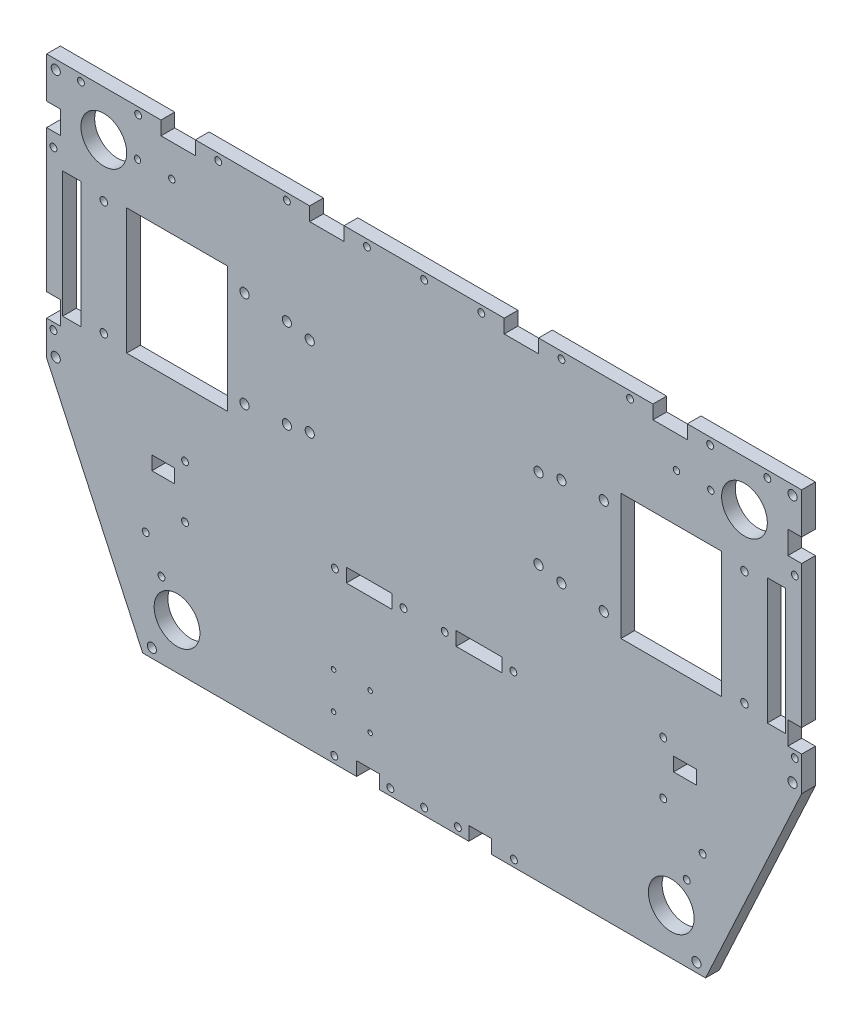
SolidWorks part; units mm, degrees
ref_plane "Plan de face" through (0, 0, 0) normal (0, 0, 1) x (1, 0, 0)
ref_plane "Plan de dessus" through (0, 0, 0) normal (0, 1, 0) x (1, 0, 0)
ref_plane "Plan de droite" through (0, 0, 0) normal (1, 0, 0) x (0, 0, -1)
sketch "Esquisse1" plane through (0, 0, 0) normal (0, 0, 1) x (1, 0, 0)
  line L0 (0, 124.9429) -> (0, -204.46) construction
  line L1 (-165, 96.73) -> (165, 96.73)
  line L2 (165, 96.73) -> (165, -18.27)
  line L3 (165, -18.27) -> (123, -109.0224)
  line L4 (123, -109.0224) -> (-123, -109.0224)
  line L5 (-211.9802, 0) -> (248.5953, 0) construction
  line L6 (-123, -109.0224) -> (-165, -18.27)
  line L7 (-165, -18.27) -> (-165, 96.73)
  line L8 (32.2623, 96.73) -> (32.2623, -70.27) construction
  circle A0 centre (-23.6, -89.5224) radius 1
  circle A1 centre (-23.6, -73.5224) radius 1
  circle A2 centre (-39.6, -89.5224) radius 1
  circle A3 centre (-39.6, -73.5224) radius 1
  dimension "D15" = 2
  dimension "D16" = 2
  dimension "D17" = 2
  dimension "D18" = 2
  dimension "D24" = 83.4
  dimension "D2" = 165
  dimension "D3" = 330
  dimension "D4" = 100
  dimension "D5" = 115
  dimension "D6" = 100
  dimension "D7" = 246
  dimension "D8" = 205.7524
  dimension "D9" = 96.73
  dimension "D10" = 115
  dimension "D11" = 167
  dimension "D19" = 19.5
  dimension "D20" = 16
  dimension "D21" = 16
  dimension "D22" = 16
  dimension "D23" = 16
extrude "Boss.-Extru.1" add sketch "Esquisse1" along normal blind 6
sketch "Esquisse2" plane through (0, 0, 6) normal (0, 0, 1) x (1, 0, 0)
  line L0 (-123, -109.0224) -> (123, -109.0224) construction
  line L1 (-158, 55.9776) -> (-150, 55.9776)
  line L2 (-158, 55.9776) -> (-158, 0.9776)
  line L3 (-158, 0.9776) -> (-150, 0.9776)
  line L4 (-150, 55.9776) -> (-150, 0.9776)
  line L5 (-130, 55.9776) -> (-86, 55.9776)
  line L6 (-130, 55.9776) -> (-130, 0.9776)
  line L7 (-130, 0.9776) -> (-86, 0.9776)
  line L8 (-86, 55.9776) -> (-86, 0.9776)
  line L9 (0, 145.0258) -> (0, -189.2208) construction
  line L10 (86, 55.9776) -> (86, 0.9776)
  line L11 (130, 0.9776) -> (86, 0.9776)
  line L12 (130, 55.9776) -> (130, 0.9776)
  line L13 (130, 55.9776) -> (86, 55.9776)
  line L14 (150, 55.9776) -> (150, 0.9776)
  line L15 (158, 0.9776) -> (150, 0.9776)
  line L16 (158, 55.9776) -> (158, 0.9776)
  line L17 (158, 55.9776) -> (150, 55.9776)
  line L18 (108, -89.0224) -> (127.6841, -51.1231) construction
  line L27 (-165, 96.73) -> (-165, -18.27) construction
  line L28 (-123, -109.0224) -> (123, -109.0224) construction
  line L29 (165, -18.27) -> (165, 96.73) construction
  line L30 (165, 96.73) -> (-165, 96.73) construction
  circle A0 centre (140, 76.73) radius 10
  circle A1 centre (108, -89.0224) radius 10
  circle A2 centre (-140, 76.73) radius 10
  circle A3 centre (-108, -89.0224) radius 10
  circle A4 centre (161, -16.0224) radius 2
  circle A5 centre (119, -105.0224) radius 2
  circle A6 centre (161, 92.73) radius 2
  circle A7 centre (-161, 92.73) radius 2
  circle A8 centre (-161, -16.0224) radius 2
  circle A9 centre (-119, -105.0224) radius 2
  circle A10 centre (125.27, 76.73) radius 1.4
  circle A11 centre (110.27, 76.73) radius 1.4
  circle A12 centre (114.7893, -75.9504) radius 1.5
  circle A13 centre (121.7031, -62.6388) radius 1.5
  circle A14 centre (-110.27, 76.73) radius 1.4
  circle A15 centre (-125.27, 76.73) radius 1.4
  circle A16 centre (-121.7031, -62.6388) radius 1.5
  circle A17 centre (-114.7893, -75.9504) radius 1.5
  dimension "D16" = 20
  dimension "D17" = 20
  dimension "D18" = 15
  dimension "D19" = 20
  dimension "D20" = 25
  dimension "D21" = 20
  dimension "D24" = 4
  dimension "D15" = 4
  dimension "D25" = 4
  dimension "D28" = 4
  dimension "D29" = 4
  dimension "D30" = 2.8
  dimension "D31" = 2.8
  dimension "D34" = 3
  dimension "D35" = 3
  dimension "D2" = 8
  dimension "D3" = 20
  dimension "D4" = 44
  dimension "D5" = 86
  dimension "D6" = 55
  dimension "D7" = 55
  dimension "D8" = 110
  dimension "D9" = 110
  dimension "D14" = 7
  dimension "D22" = 4
  dimension "D23" = 4
  dimension "D26" = 17
  dimension "D27" = 4
  dimension "D32" = 14.73
  dimension "D33" = 15
  dimension "D36" = 14.73
  dimension "D37" = 15
  dimension "D38" = 37.3159
extrude "Enlèv. mat.-Extru.1" cut sketch "Esquisse2" against normal blind 6
sketch "Esquisse3" plane through (0, 0, 0) normal (0, 0, -1) x (-1, 0, 0)
  line L0 (165, 96.73) -> (165, -18.27) construction
  line L1 (165, -3.27) -> (159, -3.27)
  line L2 (165, -3.27) -> (165, 6.73)
  line L3 (165, 6.73) -> (159, 6.73)
  line L4 (159, -3.27) -> (159, 6.73)
  line L5 (123, -109.0224) -> (-123, -109.0224) construction
  line L6 (165, 68.8526) -> (159, 68.8526)
  line L7 (165, 68.8526) -> (165, 78.8526)
  line L8 (165, 78.8526) -> (159, 78.8526)
  line L9 (159, 68.8526) -> (159, 78.8526)
  line L10 (29.5, -109.0224) -> (19.5, -109.0224)
  line L11 (29.5, -109.0224) -> (29.5, -103.0224)
  line L12 (29.5, -103.0224) -> (19.5, -103.0224)
  line L13 (19.5, -109.0224) -> (19.5, -103.0224)
  line L15 (0, -209.4812) -> (0, 177.1799) construction
  line L17 (150, 55.9776) -> (158, 55.9776) construction
  line L18 (-19.5, -109.0224) -> (-19.5, -103.0224)
  line L19 (-29.5, -103.0224) -> (-19.5, -103.0224)
  line L20 (-29.5, -109.0224) -> (-29.5, -103.0224)
  line L21 (-29.5, -109.0224) -> (-19.5, -109.0224)
  line L22 (-159, 68.8526) -> (-159, 78.8526)
  line L23 (-165, 78.8526) -> (-159, 78.8526)
  line L24 (-165, 68.8526) -> (-165, 78.8526)
  line L25 (-165, 68.8526) -> (-159, 68.8526)
  line L26 (-159, -3.27) -> (-159, 6.73)
  line L27 (-165, 6.73) -> (-159, 6.73)
  line L28 (-165, -3.27) -> (-165, 6.73)
  line L29 (-165, -3.27) -> (-159, -3.27)
  line L30 (-165, 96.73) -> (165, 96.73) construction
  line L31 (115, 96.73) -> (100, 96.73)
  line L32 (115, 96.73) -> (115, 90.73)
  line L33 (115, 90.73) -> (100, 90.73)
  line L34 (100, 96.73) -> (100, 90.73)
  line L35 (-35, 96.73) -> (-35, 90.73)
  line L36 (50, 96.73) -> (35, 96.73)
  line L37 (50, 96.73) -> (50, 90.73)
  line L38 (50, 90.73) -> (35, 90.73)
  line L39 (35, 96.73) -> (35, 90.73)
  line L40 (-50, 90.73) -> (-35, 90.73)
  line L41 (-50, 96.73) -> (-50, 90.73)
  line L42 (-50, 96.73) -> (-35, 96.73)
  line L43 (-100, 96.73) -> (-100, 90.73)
  line L44 (-115, 90.73) -> (-100, 90.73)
  line L45 (-115, 96.73) -> (-115, 90.73)
  line L46 (-115, 96.73) -> (-100, 96.73)
  dimension "D1" = 10
  dimension "D2" = 6
  dimension "D3" = 6
  dimension "D4" = 10
  dimension "D5" = 10
  dimension "D6" = 6
  dimension "D7" = 19.5
  dimension "D8" = 15
  dimension "D9" = 12.875
  dimension "D10" = 15
  dimension "D11" = 15
  dimension "D12" = 50
  dimension "D13" = 50
  dimension "D14" = 6
extrude "Enlèv. mat.-Extru.2" cut sketch "Esquisse3" against normal blind 6
sketch "Esquisse4" plane through (0, 0, 0) normal (0, 0, -1) x (-1, 0, 0)
  line L0 (159, 68.8526) -> (165, 68.8526) construction
  line L1 (13.1585, 93.73) -> (156.271, 93.73) construction
  line L2 (54.0695, -106.0224) -> (4.75, -106.0224) construction
  line L3 (123, -109.0224) -> (29.5, -109.0224) construction
  line L5 (19.5, -103.0224) -> (19.5, -109.0224) construction
  line L6 (159, -3.27) -> (165, -3.27) construction
  line L7 (29.5, -109.0224) -> (29.5, -103.0224) construction
  line L8 (165, 68.8526) -> (165, 6.73) construction
  line L13 (115, 90.73) -> (115, 96.73) construction
  line L14 (100, 96.73) -> (100, 90.73) construction
  line L15 (50, 90.73) -> (50, 96.73) construction
  line L16 (35, 96.73) -> (35, 90.73) construction
  line L17 (0, 142.2997) -> (0, -202.2086) construction
  circle A0 centre (162, -6.27) radius 1.5
  circle A1 centre (0, -106.0224) radius 1.5
  circle A2 centre (162, 62.8526) radius 1.5
  circle A3 centre (0, 93.73) radius 1.5
  circle A4 centre (-39.25, -106.0224) radius 1.5
  circle A5 centre (-14.75, -106.0224) radius 1.5
  circle A7 centre (14.75, -106.0224) radius 1.5
  circle A9 centre (39.25, -106.0224) radius 1.5
  circle A10 centre (150, 93.73) radius 1.5
  circle A11 centre (125, 93.73) radius 1.5
  circle A12 centre (90, 93.73) radius 1.5
  circle A13 centre (-25, 93.73) radius 1.5
  circle A14 centre (60, 93.73) radius 1.5
  circle A15 centre (25, 93.73) radius 1.5
  circle A16 centre (-60, 93.73) radius 1.5
  circle A17 centre (-90, 93.73) radius 1.5
  circle A18 centre (-125, 93.73) radius 1.5
  circle A19 centre (-150, 93.73) radius 1.5
  circle A31 centre (-162, 62.8526) radius 1.5
  circle A33 centre (-162, -6.27) radius 1.5
  dimension "D3" = 3
  dimension "D10" = 9.75
  dimension "D11" = 3
  dimension "D13" = 3
  dimension "D18" = 3
  dimension "D19" = 3
  dimension "D29" = 3
  dimension "D30" = 3
  dimension "D31" = 3
  dimension "D33" = 3
  dimension "D34" = 3
  dimension "D40" = 10
  dimension "D5" = 3
  dimension "D7" = 3
  dimension "D8" = 3
  dimension "D6" = 6
  dimension "D9" = 3
  dimension "D17" = 4.75
  dimension "D26" = 3
  dimension "D36" = 25
  dimension "D37" = 10
  dimension "D38" = 10
  dimension "D42" = 10
extrude "Enlèv. mat.-Extru.3" cut sketch "Esquisse4" against normal blind 6
sketch "Esquisse5" plane through (0, 0, 0) normal (0, 0, -1) x (-1, 0, 0)
  line L1 (109, -38.0224) -> (119, -38.0224)
  line L2 (109, -38.0224) -> (109, -32.0224)
  line L3 (109, -32.0224) -> (119, -32.0224)
  line L4 (119, -38.0224) -> (119, -32.0224)
  line L5 (0, -159.6455) -> (0, 113.5094) construction
  line L6 (34, -38.0224) -> (14, -38.0224)
  line L7 (34, -38.0224) -> (34, -32.0224)
  line L8 (34, -32.0224) -> (14, -32.0224)
  line L9 (14, -38.0224) -> (14, -32.0224)
  line L11 (-14, -38.0224) -> (-14, -32.0224)
  line L12 (-34, -32.0224) -> (-14, -32.0224)
  line L13 (-34, -38.0224) -> (-34, -32.0224)
  line L14 (-34, -38.0224) -> (-14, -38.0224)
  line L15 (-119, -38.0224) -> (-119, -32.0224)
  line L16 (-109, -32.0224) -> (-119, -32.0224)
  line L17 (-109, -38.0224) -> (-109, -32.0224)
  line L18 (-109, -38.0224) -> (-119, -38.0224)
  line L20 (165, -3.27) -> (165, -18.27) construction
  dimension "D1" = 10
  dimension "D2" = 20
  dimension "D3" = 56
  dimension "D4" = 6
  dimension "D5" = 6
  dimension "D6" = 75
extrude "Enlèv. mat.-Extru.4" cut sketch "Esquisse5" against normal blind 6
sketch "Esquisse6" plane through (0, 0, 0) normal (0, 0, -1) x (-1, 0, 0)
  line L0 (119, -32.0224) -> (109, -32.0224) construction
  line L1 (-165, 6.73) -> (-165, 68.8526) construction
  line L2 (0, 127.7926) -> (0, -140.3318) construction
  line L3 (-42.2546, -35.0224) -> (44.6597, -35.0224) construction
  line L4 (-86, 0.9776) -> (-130, 0.9776) construction
  line L5 (34, -38.0224) -> (34, -32.0224) construction
  line L6 (14, -32.0224) -> (14, -38.0224) construction
  line L7 (-78.5, 7.4776) -> (-78.5, 49.4776) construction
  line L8 (78.5, 7.4776) -> (78.5, 49.4776) construction
  line L10 (113.2167, -35.0224) -> (-121.7916, -35.0224) construction
  line L11 (-130, 55.9776) -> (-86, 55.9776) construction
  line L12 (-50, 45.9776) -> (50, 45.9776) construction
  line L13 (-60, 47.9776) -> (60, 47.9776) construction
  line L14 (-60, 47.9776) -> (-60, 8.9779) construction
  line L15 (-60, 8.9779) -> (60, 8.9779) construction
  line L16 (60, 47.9776) -> (60, 8.9779) construction
  line L17 (165, -3.27) -> (165, -18.27) construction
  line L18 (-50, 45.9776) -> (-50, 10.9776) construction
  line L19 (-86, 55.9776) -> (-86, 0.9776) construction
  line L20 (-50, 10.9776) -> (50, 10.9776) construction
  line L21 (50, 45.9776) -> (50, 10.9776) construction
  line L22 (-150, 0.9776) -> (-158, 0.9776) construction
  line L24 (104.5, -23.4199) -> (104.5, -49.9442) construction
  circle A0 centre (-140, 3.4776) radius 1.65
  circle A1 centre (-140, 53.4776) radius 1.65
  circle A2 centre (140, 53.4776) radius 1.65
  circle A3 centre (140, 3.4776) radius 1.65
  circle A4 centre (-39, -35.0224) radius 1.5
  circle A5 centre (9, -35.0224) radius 1.5
  circle A6 centre (39, -35.0224) radius 1.5
  circle A7 centre (-9, -35.0224) radius 1.5
  circle A8 centre (-78.5, 49.4776) radius 2
  circle A9 centre (-78.5, 7.4776) radius 2
  circle A12 centre (-60, 47.9776) radius 2
  circle A13 centre (-60, 8.9779) radius 2
  circle A14 centre (60, 8.9779) radius 2
  circle A15 centre (60, 47.9776) radius 2
  circle A16 centre (-50, 45.9776) radius 2
  circle A17 centre (50, 45.9776) radius 2
  circle A18 centre (50, 10.9776) radius 2
  circle A19 centre (-50, 10.9776) radius 2
  circle A20 centre (78.5, 7.4776) radius 2
  circle A21 centre (78.5, 49.4776) radius 2
  circle A22 centre (104.5, -27.2224) radius 1.5
  circle A23 centre (104.5, -50.2224) radius 1.5
  circle A24 centre (-104.5, -50.2224) radius 1.5
  circle A25 centre (-104.5, -27.2224) radius 1.5
  point P51 (-86, 28.4776)
  dimension "D1" = 3.3
  dimension "D2" = 3.3
  dimension "D7" = 3
  dimension "D8" = 3
  dimension "D9" = 5
  dimension "D11" = 4
  dimension "D12" = 4
  dimension "D13" = 42
  dimension "D14" = 6.5
  dimension "D15" = 4.8
  dimension "D16" = 3
  dimension "D17" = 8
  dimension "D18" = 4
  dimension "D19" = 26
  dimension "D20" = 4
  dimension "D21" = 4
  dimension "D22" = 4
  dimension "D29" = 4
  dimension "D30" = 4
  dimension "D31" = 4
  dimension "D32" = 4
  dimension "D34" = 2.5
  dimension "D38" = 3
  dimension "D4" = 25
  dimension "D5" = 25
  dimension "D6" = 50
  dimension "D10" = 5
  dimension "D23" = 120
  dimension "D24" = 38.9997
  dimension "D25" = 100
  dimension "D26" = 35
  dimension "D27" = 36
  dimension "D28" = 10
  dimension "D33" = 7.5
  dimension "D35" = 60.5
  dimension "D37" = 23
extrude "Enlèv. mat.-Extru.5" cut sketch "Esquisse6" against normal blind 6
